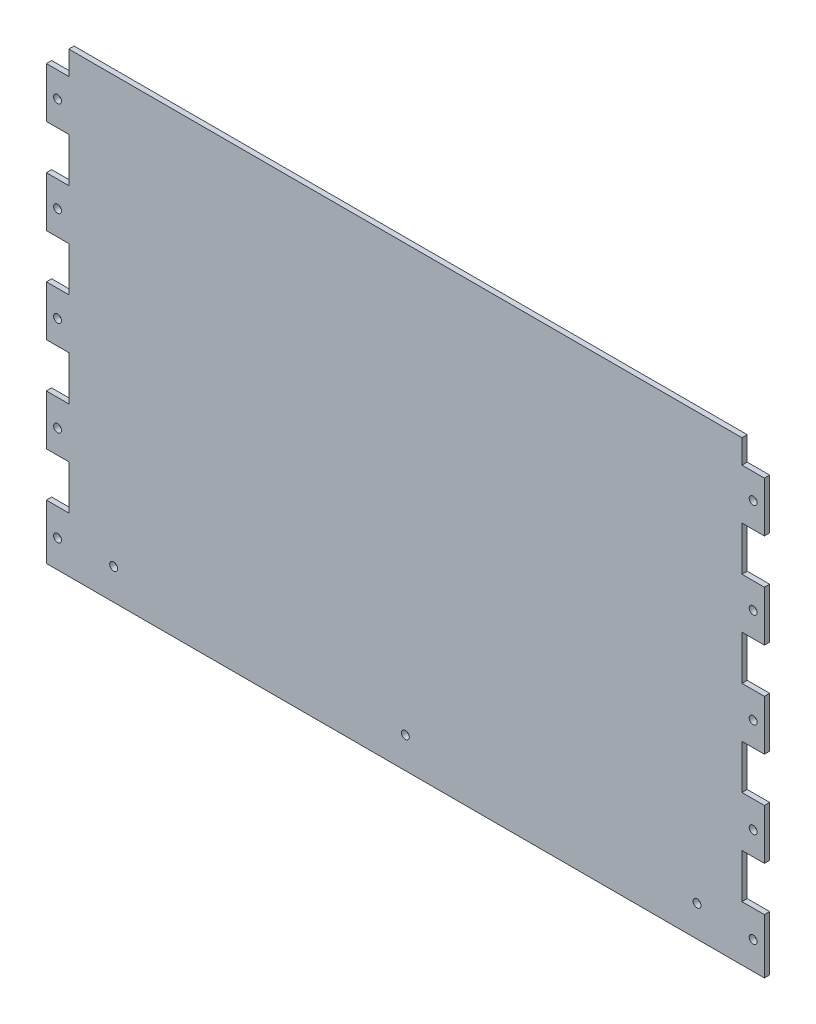
SolidWorks part; units mm, degrees
ref_plane "Front Plane" through (0, 0, 0) normal (0, 0, 1) x (1, 0, 0)
ref_plane "Top Plane" through (0, 0, 0) normal (0, 1, 0) x (1, 0, 0)
ref_plane "Right Plane" through (0, 0, 0) normal (1, 0, 0) x (0, 0, -1)
sketch "Sketch1" plane through (0, 0, 0) normal (0, 0, 1) x (1, 0, 0)
  line L0 (0, 20.8) -> (8.5, 20.8)
  line L1 (0, 0) -> (272, 0)
  line L2 (0, 0) -> (0, 20.8)
  line L3 (8.5, 173) -> (263.5, 173)
  line L4 (272, 0) -> (272, 20.8)
  line L5 (8.5, 20.8) -> (8.5, 37.6)
  line L6 (8.5, 37.6) -> (0, 37.6)
  line L7 (0, 56.6) -> (8.5, 56.6)
  line L8 (8.5, 56.6) -> (8.5, 73.4)
  line L9 (8.5, 73.4) -> (0, 73.4)
  line L10 (0, 92.4) -> (8.5, 92.4)
  line L11 (8.5, 92.4) -> (8.5, 109.2)
  line L12 (8.5, 109.2) -> (0, 109.2)
  line L13 (0, 128.2) -> (8.5, 128.2)
  line L14 (8.5, 128.2) -> (8.5, 145)
  line L15 (8.5, 145) -> (0, 145)
  line L16 (0, 164) -> (8.5, 164)
  line L17 (8.5, 164) -> (8.5, 173)
  line L18 (0, 145) -> (0, 164)
  line L19 (0, 109.2) -> (0, 128.2)
  line L20 (0, 73.4) -> (0, 92.4)
  line L21 (0, 37.6) -> (0, 56.6)
  line L22 (136, 0) -> (136, 173) construction
  line L23 (263.5, 128.2) -> (263.5, 145)
  line L24 (263.5, 92.4) -> (263.5, 109.2)
  line L25 (263.5, 56.6) -> (263.5, 73.4)
  line L26 (263.5, 20.8) -> (263.5, 37.6)
  line L27 (272, 20.8) -> (263.5, 20.8)
  line L28 (263.5, 37.6) -> (272, 37.6)
  line L29 (272, 56.6) -> (263.5, 56.6)
  line L30 (263.5, 73.4) -> (272, 73.4)
  line L31 (272, 92.4) -> (263.5, 92.4)
  line L32 (263.5, 109.2) -> (272, 109.2)
  line L33 (272, 128.2) -> (263.5, 128.2)
  line L34 (263.5, 145) -> (272, 145)
  line L35 (272, 164) -> (263.5, 164)
  line L36 (263.5, 164) -> (263.5, 173)
  line L37 (272, 145) -> (272, 164)
  line L38 (272, 109.2) -> (272, 128.2)
  line L39 (272, 73.4) -> (272, 92.4)
  line L40 (272, 37.6) -> (272, 56.6)
  circle A0 centre (4.25, 154.5) radius 1.5
  circle A1 centre (4.25, 118.5) radius 1.5
  circle A2 centre (4.25, 82.5) radius 1.5
  circle A3 centre (4.25, 46.5) radius 1.5
  circle A4 centre (4.25, 10.5) radius 1.5
  circle A5 centre (267.75, 10.5) radius 1.5
  circle A6 centre (267.75, 46.5) radius 1.5
  circle A7 centre (267.75, 82.5) radius 1.5
  circle A8 centre (267.75, 118.5) radius 1.5
  circle A9 centre (267.75, 154.5) radius 1.5
  circle A10 centre (25.5, 11.75) radius 1.5
  circle A11 centre (136, 11.75) radius 1.5
  circle A12 centre (246.5, 11.75) radius 1.5
  point P11 (4.25, 56.6)
  point P28 (0, 154.5)
  point P67 (0, 0)
  point P68 (0, 0)
  dimension "D10" = 4.25
  dimension "D11" = 3
  dimension "D13" = 3
  dimension "D1" = 272
  dimension "D2" = 173
  dimension "D3" = 8.5
  dimension "D4" = 20.8
  dimension "D5" = 16.8
  dimension "D6" = 19
  dimension "D7" = 19
  dimension "D8" = 19
  dimension "D9" = 19
  dimension "D14" = 17
  dimension "D15" = 11.75
  dimension "D17" = 21.25
  dimension "D12" = 5
  dimension "D16" = 3
extrude "Boss-Extrude1" add sketch "Sketch1" along normal blind 2
